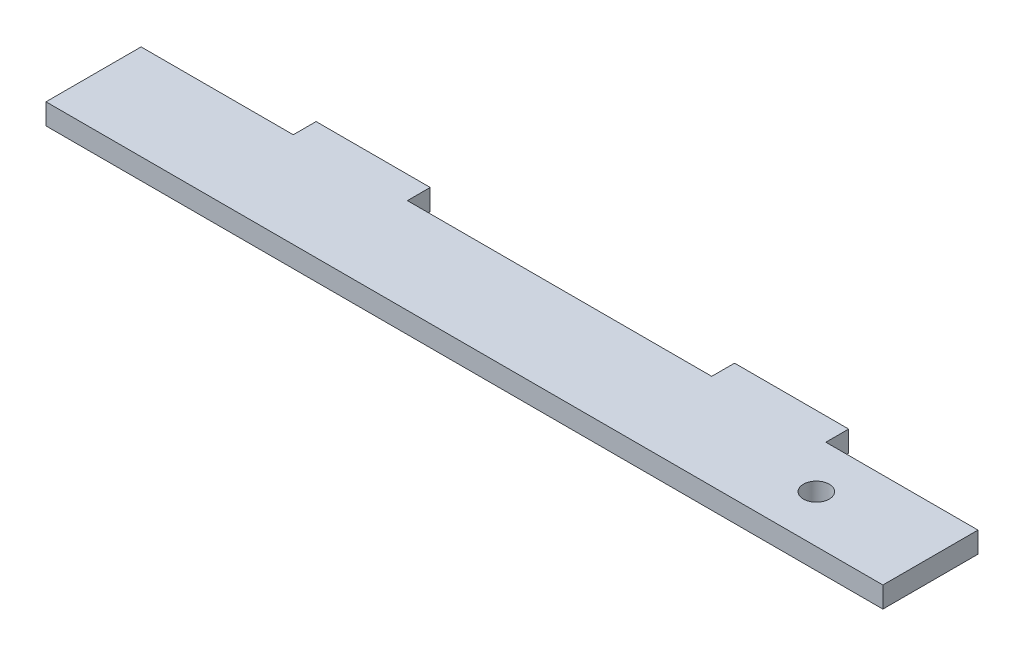
SolidWorks part; units mm, degrees
ref_plane "Front Plane" through (0, 0, 0) normal (0, 0, 1) x (1, 0, 0)
ref_plane "Top Plane" through (0, 0, 0) normal (0, 1, 0) x (1, 0, 0)
ref_plane "Right Plane" through (0, 0, 0) normal (1, 0, 0) x (0, 0, -1)
sketch "Sketch1" plane through (0, 0, 0) normal (0, 1, 0) x (1, 0, 0)
  line L0 (0, -55) -> (0, 55) construction
  line L1 (-110, -12.5) -> (110, -12.5)
  line L2 (-110, -12.5) -> (-110, 12.5)
  line L3 (-110, 12.5) -> (110, 12.5)
  line L4 (110, -12.5) -> (110, 12.5)
  line L5 (-110, -12.5) -> (110, 12.5) construction
  line L6 (-110, 12.5) -> (110, -12.5) construction
  line L7 (-70, 12.5) -> (-40, 12.5)
  line L8 (-70, 12.5) -> (-70, 18.5)
  line L9 (-70, 18.5) -> (-40, 18.5)
  line L10 (-40, 12.5) -> (-40, 18.5)
  line L11 (40, 12.5) -> (40, 18.5)
  line L12 (70, 12.5) -> (70, 18.5)
  line L13 (70, 18.5) -> (40, 18.5)
  point P0 (0, 0)
  dimension "D1" = 25
  dimension "D2" = 220
  dimension "D3" = 40
  dimension "D4" = 6
  dimension "D5" = 30
extrude "Boss-Extrude1" add sketch "Sketch1" along normal blind 5.5 contours L3 L10 L9 L8 | L1 L4 L3 L2 | L12 L13 L11 L3
sketch "Sketch3" plane through (0, 5.5, 0) normal (0, 1, 0) x (1, 0, 0)
  line L0 (-3.025, 0) -> (3.025, 0) construction
  line L1 (110, -12.5) -> (110, 12.5) construction
  circle A0 centre (80, 0) radius 3.4
  dimension "D1" = 6.8
  dimension "D2" = 30
extrude "Cut-Extrude1" cut sketch "Sketch3" against normal through all
